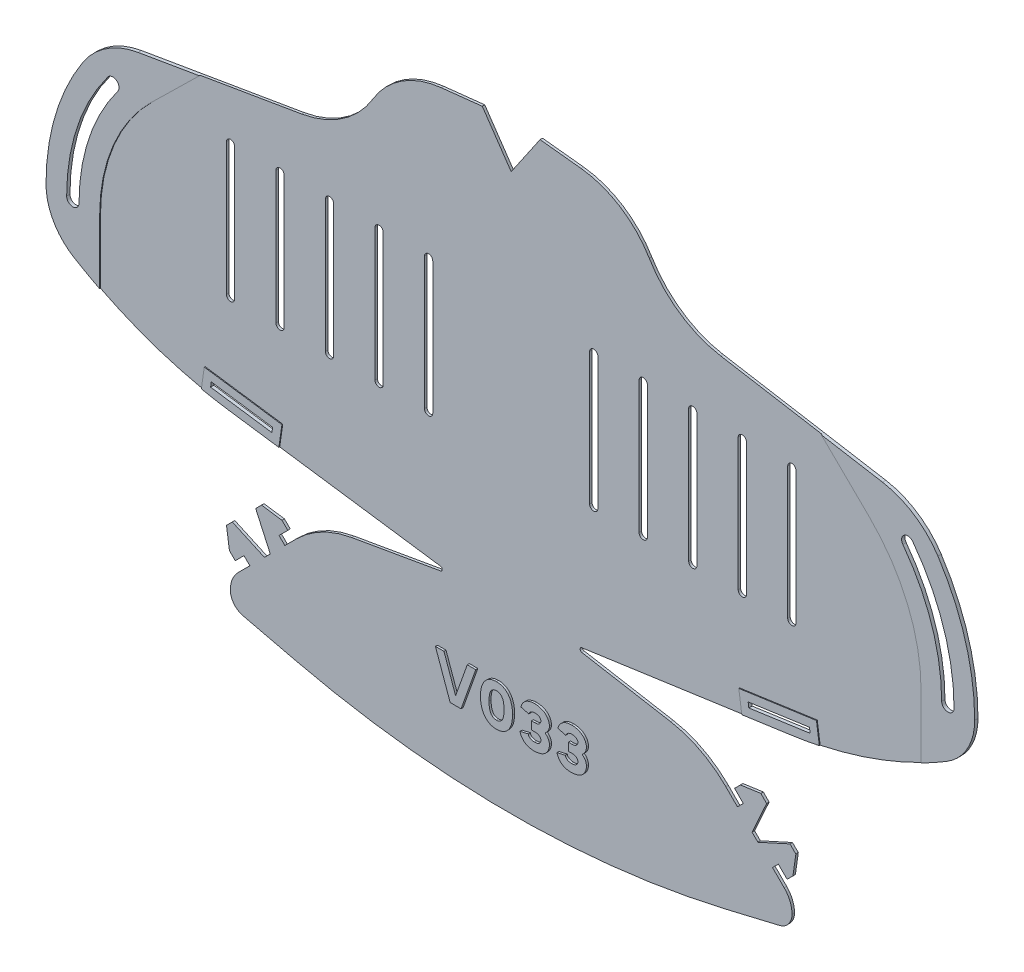
SolidWorks part; units mm, degrees
ref_plane "Front Plane" through (0, 0, 0) normal (0, 0, 1) x (1, 0, 0)
ref_plane "Top Plane" through (0, 0, 0) normal (0, 1, 0) x (1, 0, 0)
ref_plane "Right Plane" through (0, 0, 0) normal (1, 0, 0) x (0, 0, -1)
sketch "Sketch1" plane through (0, 0, 0) normal (0, 0, 1) x (1, 0, 0)
  line L0 (0, 0) -> (0, -145) construction
  line L1 (-14, -102) -> (14, -102) construction
  line L2 (-112.5, -69) -> (112.5, -69) construction
  line L3 (0, -10.2352) -> (-7, 0)
  line L4 (0, -10.2352) -> (7, 0)
  line L5 (7, 0) -> (16.9419, -1.0768)
  line L6 (-90.1804, -30.1909) -> (-50.7439, -23.5)
  line L7 (90.1804, -30.1909) -> (50.7439, -23.5)
  line L8 (-14, -102) -> (-68.2662, -94.2919)
  line L9 (-7, 0) -> (-16.9419, -1.0768)
  line L10 (14, -102) -> (68.2662, -94.2919)
  line L11 (-103.5977, -39) -> (-103.5977, -69) construction
  line L12 (-14, -102) -> (-38.6266, -106.305)
  line L13 (-52, -113.2546) -> (-54.8283, -116.0832)
  line L14 (52, -113.2546) -> (54.8283, -116.0832)
  line L15 (14, -102) -> (38.6266, -106.305)
  line L16 (-54.8283, -116.0832) -> (-56.2426, -114.669)
  line L17 (-56.2426, -114.669) -> (-54.1214, -112.5476)
  line L18 (-54.1214, -112.5476) -> (-55.5356, -111.1334)
  line L19 (-55.5356, -111.1334) -> (-60.4854, -110.4265)
  line L20 (-60.4854, -110.4265) -> (-68.9703, -118.9122)
  line L21 (-64.7275, -123.1546) -> (-63.3132, -124.5688)
  line L22 (-63.3132, -124.5688) -> (-66.1415, -127.3973)
  line L23 (-64.7275, -123.1546) -> (-66.8487, -125.2761)
  line L24 (-66.8487, -125.2761) -> (-68.263, -123.8619)
  line L25 (-68.9703, -118.9122) -> (-68.263, -123.8619)
  line L26 (68.9703, -118.9122) -> (68.263, -123.8619)
  line L27 (66.8487, -125.2761) -> (68.263, -123.8619)
  line L28 (64.7275, -123.1546) -> (66.8487, -125.2761)
  line L29 (63.3132, -124.5688) -> (66.1415, -127.3973)
  line L30 (64.7275, -123.1546) -> (63.3132, -124.5688)
  line L31 (60.4854, -110.4265) -> (68.9703, -118.9122)
  line L32 (55.5356, -111.1334) -> (60.4854, -110.4265)
  line L33 (54.1214, -112.5476) -> (55.5356, -111.1334)
  line L34 (56.2426, -114.669) -> (54.1214, -112.5476)
  line L35 (54.8283, -116.0832) -> (56.2426, -114.669)
  line L36 (-64.9691, -135.8852) -> (-52.4361, -138.8607)
  line L37 (64.9691, -135.8852) -> (52.4361, -138.8607)
  line L38 (-68.9703, -118.9122) -> (-64.7275, -123.1546) construction
  line L39 (-60.4854, -110.4265) -> (-56.2426, -114.669) construction
  arc A0 (-16.9419, -1.0768) -> (-33.4614, -11.6696) centre (-14.5729, -22.9489) ccw
  arc A1 (-33.4614, -11.6696) -> (-50.7439, -23.5) centre (-54.9257, 1.1478) cw
  arc A2 (-103.5977, -39) -> (-90.1804, -30.1909) centre (-86.8349, -49.9091) cw
  arc A3 (-112.5, -69) -> (-103.5977, -39) centre (-57.5, -69) cw
  arc A4 (112.5, -69) -> (103.5977, -39) centre (57.5, -69) ccw
  arc A5 (103.5977, -39) -> (90.1804, -30.1909) centre (86.8349, -49.9091) ccw
  arc A6 (16.9419, -1.0768) -> (33.4614, -11.6696) centre (14.5729, -22.9489) cw
  arc A7 (33.4614, -11.6696) -> (50.7439, -23.5) centre (54.9257, 1.1478) ccw
  arc A8 (-112.5, -69) -> (-105.7111, -81) centre (-98.5, -69) ccw
  arc A9 (-105.7111, -81) -> (-68.2662, -94.2919) centre (-54.2032, 4.7143) ccw
  arc A10 (112.5, -69) -> (105.7111, -81) centre (98.5, -69) cw
  arc A11 (105.7111, -81) -> (68.2662, -94.2919) centre (54.2032, 4.7143) cw
  arc A12 (-38.6266, -106.305) -> (-52, -113.2546) centre (-34.3216, -130.9315) ccw
  arc A13 (38.6266, -106.305) -> (52, -113.2546) centre (34.3216, -130.9315) cw
  arc A14 (-66.1415, -127.3973) -> (-68.0451, -131.9933) centre (-61.5451, -131.9933) ccw
  arc A15 (-68.0451, -131.9933) -> (-64.9691, -135.8852) centre (-64.0451, -131.9933) ccw
  arc A16 (68.0451, -131.9933) -> (64.9691, -135.8852) centre (64.0451, -131.9933) cw
  arc A17 (66.1415, -127.3973) -> (68.0451, -131.9933) centre (61.5451, -131.9933) cw
  arc A19 (-52.4361, -138.8607) -> (0, -145) centre (0, 82) ccw
  arc A20 (52.4361, -138.8607) -> (0, -145) centre (0, 82) cw
  point P8 (0, -102)
  point P11 (0, -69)
  dimension "D5" = 55
  dimension "D11" = 20
  dimension "D13" = 25
  dimension "D16" = 14
  dimension "D15" = 22
  dimension "D18" = 100
  dimension "D22" = 25
  dimension "D31" = 6.5
  dimension "D32" = 4
  dimension "D34" = 227
  dimension "D1" = 145
  dimension "D2" = 28
  dimension "D3" = 43
  dimension "D4" = 76
  dimension "D6" = 225
  dimension "D7" = 14
  dimension "D8" = 12.4
  dimension "D9" = 10
  dimension "D10" = 30
  dimension "D12" = 40
  dimension "D14" = 45.5
  dimension "D17" = 12
  dimension "D19" = 18
  dimension "D20" = 25
  dimension "D21" = 4
  dimension "D23" = 38
  dimension "D24" = 2
  dimension "D25" = 3
  dimension "D26" = 2
  dimension "D27" = 18
  dimension "D29" = 8
  dimension "D30" = 4
extrude "Main Shape" add sketch "Sketch1" along normal blind 0.6
sketch "Sketch2" plane through (0, 0, 0.6) normal (0, 0, 1) x (1, 0, 0)
  line L0 (0, -55) -> (0, 55) construction
  arc A0 (-96.3, -39.9) -> (-106, -69) centre (-57.5, -69) ccw construction
  arc A1 (-97.5, -39) -> (-107.5, -69) centre (-57.5, -69) ccw
  arc A2 (-95.1, -40.8) -> (-104.5, -69) centre (-57.5, -69) ccw
  arc A3 (-95.1, -40.8) -> (-97.5, -39) centre (-96.3, -39.9) ccw
  arc A4 (-107.5, -69) -> (-104.5, -69) centre (-106, -69) ccw
  arc A6 (-103.5977, -39) -> (-112.5, -69) centre (-57.5, -69) ccw construction
  arc A7 (96.3, -39.9) -> (106, -69) centre (57.5, -69) cw construction
  arc A8 (97.5, -39) -> (107.5, -69) centre (57.5, -69) cw
  arc A9 (95.1, -40.8) -> (104.5, -69) centre (57.5, -69) cw
  arc A10 (95.1, -40.8) -> (97.5, -39) centre (96.3, -39.9) cw
  arc A11 (107.5, -69) -> (104.5, -69) centre (106, -69) cw
  point P3 (-103.5111, -53.663)
  point P19 (103.5111, -53.663)
  dimension "D1" = 5
  dimension "D2" = 1.5
extrude "Elastic Attachment Points" cut sketch "Sketch2" against normal through all
sketch "Sketch7" plane through (0, 0, 0.6) normal (0, 0, 1) x (1, 0, 0)
  line L0 (-99.5, -69) -> (-99.5, -84.4384)
  line L1 (-86.8939, -39) -> (-75.3319, -27.6717)
  line L2 (-50.7439, -23.5) -> (-90.1804, -30.1909) construction
  line L3 (-75.3319, -27.6717) -> (-90.1804, -30.1909)
  line L4 (0, -55) -> (0, 55) construction
  line L5 (75.3319, -27.6717) -> (90.1804, -30.1909)
  line L6 (86.8939, -39) -> (75.3319, -27.6717)
  line L7 (99.5, -69) -> (99.5, -84.4384)
  arc A0 (-99.5, -69) -> (-86.8939, -39) centre (-57.5, -69) cw
  arc A1 (-95.1, -40.8) -> (-104.5, -69) centre (-57.5, -69) ccw construction
  arc A2 (-105.7111, -81) -> (-68.2662, -94.2919) centre (-54.2032, 4.7143) ccw construction
  arc A3 (-112.5, -69) -> (-105.7111, -81) centre (-98.5, -69) ccw construction
  arc A4 (-103.5977, -39) -> (-112.5, -69) centre (-57.5, -69) ccw construction
  arc A5 (-90.1804, -30.1909) -> (-103.5977, -39) centre (-86.8349, -49.9091) ccw construction
  arc A6 (-105.7111, -81) -> (-99.5, -84.4384) centre (-54.2032, 4.7143) ccw
  arc A7 (-112.5, -69) -> (-105.7111, -81) centre (-98.5, -69) ccw
  arc A8 (-103.5977, -39) -> (-112.5, -69) centre (-57.5, -69) ccw
  arc A9 (-90.1804, -30.1909) -> (-103.5977, -39) centre (-86.8349, -49.9091) ccw
  arc A10 (90.1804, -30.1909) -> (103.5977, -39) centre (86.8349, -49.9091) cw
  arc A11 (103.5977, -39) -> (112.5, -69) centre (57.5, -69) cw
  arc A12 (112.5, -69) -> (105.7111, -81) centre (98.5, -69) cw
  arc A13 (105.7111, -81) -> (99.5, -84.4384) centre (54.2032, 4.7143) cw
  arc A14 (99.5, -69) -> (86.8939, -39) centre (57.5, -69) ccw
  arc A15 (-107.5, -69) -> (-104.5, -69) centre (-106, -69) ccw construction
  arc A16 (-95.1, -40.8) -> (-97.5, -39) centre (-96.3, -39.9) ccw construction
  arc A17 (-97.5, -39) -> (-107.5, -69) centre (-57.5, -69) ccw construction
  arc A18 (-107.5, -69) -> (-104.5, -69) centre (-106, -69) ccw
  arc A19 (-95.1, -40.8) -> (-97.5, -39) centre (-96.3, -39.9) ccw
  arc A20 (-95.1, -40.8) -> (-104.5, -69) centre (-57.5, -69) ccw
  arc A21 (-97.5, -39) -> (-107.5, -69) centre (-57.5, -69) ccw
  arc A22 (104.5, -69) -> (107.5, -69) centre (106, -69) ccw construction
  arc A23 (97.5, -39) -> (95.1, -40.8) centre (96.3, -39.9) ccw construction
  arc A24 (104.5, -69) -> (95.1, -40.8) centre (57.5, -69) ccw construction
  arc A25 (107.5, -69) -> (97.5, -39) centre (57.5, -69) ccw construction
  arc A26 (104.5, -69) -> (107.5, -69) centre (106, -69) ccw
  arc A27 (97.5, -39) -> (95.1, -40.8) centre (96.3, -39.9) ccw
  arc A28 (104.5, -69) -> (95.1, -40.8) centre (57.5, -69) ccw
  arc A29 (107.5, -69) -> (97.5, -39) centre (57.5, -69) ccw
  dimension "D1" = 5
extrude "Reinforced Attachment Points" add sketch "Sketch7" along normal blind 0.2
sketch "Sketch6" plane through (0, 0, 0.6) normal (0, 0, 1) x (1, 0, 0)
  line L0 (-72.6274, -91.6524) -> (-57.7765, -93.7618)
  line L1 (-57.7765, -93.7618) -> (-57.6078, -92.5738)
  line L2 (-57.6078, -92.5738) -> (-72.4587, -90.4643)
  line L3 (-72.4587, -90.4643) -> (-72.6274, -91.6524)
  line L4 (-68.2662, -94.2919) -> (-14, -102) construction
  line L5 (-65.0332, -91.519) -> (-65.202, -92.7071) construction
  line L13 (0, -0.605) -> (0, 0.605) construction
  line L14 (65.0332, -91.519) -> (65.202, -92.7071) construction
  line L15 (72.6274, -91.6524) -> (72.4587, -90.4643)
  line L16 (57.6078, -92.5738) -> (57.7765, -93.7618)
  line L22 (57.6078, -92.5738) -> (72.4587, -90.4643)
  line L24 (72.6274, -91.6524) -> (57.7765, -93.7618)
  dimension "D1" = 2
  dimension "D2" = 15
  dimension "D3" = 52
  dimension "D4" = 1.2
extrude "Tab Slits" cut sketch "Sketch6" against normal through all
sketch "Sketch9" plane through (0, 0, 0.6) normal (0, 0, 1) x (1, 0, 0)
  line L4 (-57.7765, -93.7618) -> (-57.6078, -92.5738) construction
  line L5 (-72.6274, -91.6524) -> (-57.7765, -93.7618) construction
  line L6 (-72.4587, -90.4643) -> (-72.6274, -91.6524) construction
  line L7 (-57.6078, -92.5738) -> (-72.4587, -90.4643) construction
  line L12 (-57.7765, -93.7618) -> (-57.6078, -92.5738)
  line L13 (-72.6274, -91.6524) -> (-57.7765, -93.7618)
  line L14 (-72.4587, -90.4643) -> (-72.6274, -91.6524)
  line L15 (-57.6078, -92.5738) -> (-72.4587, -90.4643)
  line L16 (-56.0776, -96.0232) -> (-55.3464, -90.8749)
  line L17 (-68.2662, -94.2919) -> (-14, -102) construction
  line L18 (-55.3464, -90.8749) -> (-74.1575, -88.2029)
  line L19 (-74.1575, -88.2029) -> (-74.8573, -93.1295)
  line L20 (-68.2662, -94.2919) -> (-56.0776, -96.0232)
  line L21 (0, -0.605) -> (0, 0.605) construction
  line L22 (68.2662, -94.2919) -> (56.0776, -96.0232)
  line L23 (74.1575, -88.2029) -> (74.8573, -93.1295)
  line L24 (55.3464, -90.8749) -> (74.1575, -88.2029)
  line L25 (56.0776, -96.0232) -> (55.3464, -90.8749)
  line L26 (57.6078, -92.5738) -> (72.4587, -90.4643)
  line L27 (72.4587, -90.4643) -> (72.6274, -91.6524)
  line L28 (72.6274, -91.6524) -> (57.7765, -93.7618)
  line L29 (57.7765, -93.7618) -> (57.6078, -92.5738)
  arc A0 (-99.5, -84.4384) -> (-68.2662, -94.2919) centre (-54.2032, 4.7143) ccw construction
  arc A1 (-74.8573, -93.1295) -> (-68.2662, -94.2919) centre (-54.2032, 4.7143) ccw
  arc A2 (74.8573, -93.1295) -> (68.2662, -94.2919) centre (54.2032, 4.7143) cw
  dimension "D1" = 2
  dimension "D2" = 2
  dimension "D3" = 2
extrude "Reinforced Tab Slits" add sketch "Sketch9" along normal blind 0.2
sketch "Sketch11" plane through (0, 0, 0.6) normal (0, 0, 1) x (1, 0, 0)
  line L0 (-67.5562, -117.4979) -> (-59.7778, -121.0331)
  line L1 (-60.4854, -110.4265) -> (-68.9703, -118.9122) construction
  line L2 (-59.7778, -121.0331) -> (-58.3637, -119.6188)
  line L3 (-58.3637, -119.6188) -> (-61.8996, -111.8408)
  line L4 (-61.8996, -111.8408) -> (-67.5562, -117.4979)
  line L6 (-58.3637, -119.6188) -> (-54.8283, -116.0832) construction
  line L7 (-59.7778, -121.0331) -> (-63.3132, -124.5688) construction
  line L10 (0, -0.605) -> (0, 0.605) construction
  line L11 (59.7778, -121.0331) -> (63.3132, -124.5688) construction
  line L12 (58.3637, -119.6188) -> (54.8283, -116.0832) construction
  line L13 (61.8996, -111.8408) -> (67.5562, -117.4979)
  line L14 (58.3637, -119.6188) -> (61.8996, -111.8408)
  line L15 (59.7778, -121.0331) -> (58.3637, -119.6188)
  line L16 (67.5562, -117.4979) -> (59.7778, -121.0331)
  dimension "D1" = 2
  dimension "D2" = 2
  dimension "D3" = 5
extrude "Tab Flex Relief" cut sketch "Sketch11" against normal through all both and the other way through all
sketch "Sketch3" plane through (0, 0, 0.6) normal (0, 0, 1) x (1, 0, 0)
  line L0 (-20, -38.45) -> (-20, -70.45) construction
  line L1 (-19, -38.45) -> (-19, -70.45)
  line L2 (-21, -38.45) -> (-21, -70.45)
  line L3 (0, -10.2352) -> (0, -145) construction
  line L4 (-106, -69) -> (-96.3, -69) construction
  line L5 (-96.3, -69) -> (-96.3, -39.9) construction
  line L6 (-32, -38.45) -> (-32, -70.45) construction
  line L7 (-31, -38.45) -> (-31, -70.45)
  line L8 (-33, -38.45) -> (-33, -70.45)
  line L9 (-44, -38.45) -> (-44, -70.45) construction
  line L10 (-43, -38.45) -> (-43, -70.45)
  line L11 (-45, -38.45) -> (-45, -70.45)
  line L12 (-56, -38.45) -> (-56, -70.45) construction
  line L13 (-55, -38.45) -> (-55, -70.45)
  line L14 (-57, -38.45) -> (-57, -70.45)
  line L15 (-68, -38.45) -> (-68, -70.45) construction
  line L16 (-67, -38.45) -> (-67, -70.45)
  line L17 (-69, -38.45) -> (-69, -70.45)
  line L18 (20, -38.45) -> (20, -70.45) construction
  line L19 (19, -38.45) -> (19, -70.45)
  line L20 (21, -38.45) -> (21, -70.45)
  line L21 (32, -38.45) -> (32, -70.45) construction
  line L22 (31, -38.45) -> (31, -70.45)
  line L23 (33, -38.45) -> (33, -70.45)
  line L24 (44, -38.45) -> (44, -70.45) construction
  line L25 (43, -38.45) -> (43, -70.45)
  line L26 (45, -38.45) -> (45, -70.45)
  line L27 (56, -38.45) -> (56, -70.45) construction
  line L28 (55, -38.45) -> (55, -70.45)
  line L29 (57, -38.45) -> (57, -70.45)
  line L30 (68, -38.45) -> (68, -70.45) construction
  line L31 (67, -38.45) -> (67, -70.45)
  line L32 (69, -38.45) -> (69, -70.45)
  arc A0 (-19, -38.45) -> (-21, -38.45) centre (-20, -38.45) ccw
  arc A1 (-21, -70.45) -> (-19, -70.45) centre (-20, -70.45) ccw
  arc A2 (-52.4361, -138.8607) -> (52.4361, -138.8607) centre (0, 82) ccw construction
  arc A3 (-31, -38.45) -> (-33, -38.45) centre (-32, -38.45) ccw
  arc A4 (-33, -70.45) -> (-31, -70.45) centre (-32, -70.45) ccw
  arc A5 (-43, -38.45) -> (-45, -38.45) centre (-44, -38.45) ccw
  arc A6 (-45, -70.45) -> (-43, -70.45) centre (-44, -70.45) ccw
  arc A7 (-55, -38.45) -> (-57, -38.45) centre (-56, -38.45) ccw
  arc A8 (-57, -70.45) -> (-55, -70.45) centre (-56, -70.45) ccw
  arc A9 (-67, -38.45) -> (-69, -38.45) centre (-68, -38.45) ccw
  arc A10 (-69, -70.45) -> (-67, -70.45) centre (-68, -70.45) ccw
  arc A11 (19, -38.45) -> (21, -38.45) centre (20, -38.45) cw
  arc A12 (21, -70.45) -> (19, -70.45) centre (20, -70.45) cw
  arc A13 (31, -38.45) -> (33, -38.45) centre (32, -38.45) cw
  arc A14 (33, -70.45) -> (31, -70.45) centre (32, -70.45) cw
  arc A15 (43, -38.45) -> (45, -38.45) centre (44, -38.45) cw
  arc A16 (45, -70.45) -> (43, -70.45) centre (44, -70.45) cw
  arc A17 (55, -38.45) -> (57, -38.45) centre (56, -38.45) cw
  arc A18 (57, -70.45) -> (55, -70.45) centre (56, -70.45) cw
  arc A19 (67, -38.45) -> (69, -38.45) centre (68, -38.45) cw
  arc A20 (69, -70.45) -> (67, -70.45) centre (68, -70.45) cw
  point P2 (-20, -54.45)
  point P13 (-19, -54.45)
  point P16 (-96.3, -54.45)
  point P20 (-32, -54.45)
  point P31 (-44, -54.45)
  point P38 (-56, -54.45)
  point P45 (-68, -54.45)
  point P52 (20, -54.45)
  point P59 (32, -54.45)
  point P66 (44, -54.45)
  point P73 (56, -54.45)
  point P80 (68, -54.45)
  dimension "D1" = 2
  dimension "D2" = 32
  dimension "D3" = 20
  dimension "D4" = 5
  dimension "D5" = 10
extrude "Breathing Slits" cut sketch "Sketch3" against normal through all
sketch "Sketch8" plane through (0, 0, 0.6) normal (0, 0, 1) x (1, 0, 0)
  line L0 (-67.0266, -128.5) -> (67.0266, -128.5) construction
  line L1 (0, -10.2352) -> (0, -145) construction
  arc A0 (-52.4361, -138.8607) -> (52.4361, -138.8607) centre (0, 82) ccw construction
  arc A1 (-66.1415, -127.3973) -> (-68.0451, -131.9933) centre (-61.5451, -131.9933) ccw construction
  text T0 "<b>V033</b>" font "Double Porter 3" height 10
  point P9 (0, -128.5)
  dimension "D2" = 16.5
extrude "Version Number" add sketch "Sketch8" along normal blind 0.5
fillet "Fillet1" radius 0.5 2 edges at (-14, -102, 0.3) (14, -102, 0.3)
